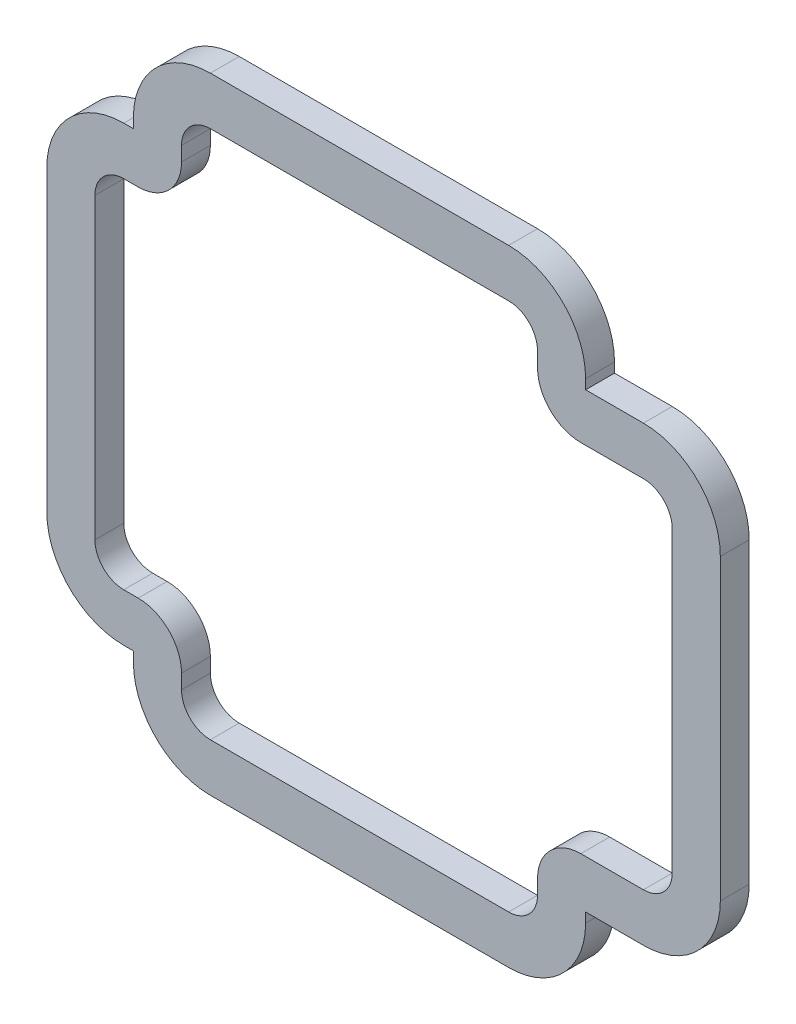
SolidWorks part; units mm, degrees
ref_plane "Plano frontal" through (0, 0, 0) normal (0, 0, 1) x (1, 0, 0)
ref_plane "Plano superior" through (0, 0, 0) normal (0, 1, 0) x (1, 0, 0)
ref_plane "Plano direito" through (0, 0, 0) normal (1, 0, 0) x (0, 0, -1)
sketch "Esboço1" plane through (0, 0, 0) normal (0, 0, 1) x (1, 0, 0)
  line L0 (46.5, -1.5) -> (46.5, -0.5)
  line L1 (46.5, -0.5) -> (52.5, -0.5)
  line L2 (60.5, 7.5) -> (60.5, 38.5)
  line L3 (52.5, 46.5) -> (46.5, 46.5)
  line L4 (46.5, 46.5) -> (46.5, 47.5)
  line L5 (38.5, 55.5) -> (7.5, 55.5)
  line L6 (-0.5, 47.5) -> (-0.5, 46.5)
  line L7 (-0.5, 46.5) -> (-1.5, 46.5)
  line L8 (-9.5, 38.5) -> (-9.5, 7.5)
  line L9 (-1.5, -0.5) -> (-0.5, -0.5)
  line L10 (-0.5, -0.5) -> (-0.5, -1.5)
  line L11 (7.5, -9.5) -> (38.5, -9.5)
  line L24 (41.5, -1.5) -> (41.5, 0)
  line L25 (46, 4.5) -> (52.5, 4.5)
  line L26 (55.5, 7.5) -> (55.5, 38.5)
  line L27 (52.5, 41.5) -> (46, 41.5)
  line L28 (41.5, 46) -> (41.5, 47.5)
  line L29 (38.5, 50.5) -> (7.5, 50.5)
  line L30 (4.5, 47.5) -> (4.5, 46)
  line L31 (0, 41.5) -> (-1.5, 41.5)
  line L32 (-4.5, 38.5) -> (-4.5, 7.5)
  line L33 (-1.5, 4.5) -> (0, 4.5)
  line L34 (4.5, 0) -> (4.5, -1.5)
  line L35 (7.5, -4.5) -> (38.5, -4.5)
  arc A2 (38.5, -9.5) -> (46.5, -1.5) centre (38.5, -1.5) ccw
  arc A3 (46.5, -0.5) -> (46.5, -0.5) centre (46.5, -0.5) ccw
  arc A4 (52.5, -0.5) -> (60.5, 7.5) centre (52.5, 7.5) ccw
  arc A5 (60.5, 38.5) -> (52.5, 46.5) centre (52.5, 38.5) ccw
  arc A6 (46.5, 46.5) -> (46.5, 46.5) centre (46.5, 46.5) ccw
  arc A7 (46.5, 47.5) -> (38.5, 55.5) centre (38.5, 47.5) ccw
  arc A8 (7.5, 55.5) -> (-0.5, 47.5) centre (7.5, 47.5) ccw
  arc A9 (-0.5, 46.5) -> (-0.5, 46.5) centre (-0.5, 46.5) ccw
  arc A10 (-1.5, 46.5) -> (-9.5, 38.5) centre (-1.5, 38.5) ccw
  arc A11 (-9.5, 7.5) -> (-1.5, -0.5) centre (-1.5, 7.5) ccw
  arc A12 (-0.5, -0.5) -> (-0.5, -0.5) centre (-0.5, -0.5) ccw
  arc A13 (-0.5, -1.5) -> (7.5, -9.5) centre (7.5, -1.5) ccw
  arc A26 (38.5, -4.5) -> (41.5, -1.5) centre (38.5, -1.5) ccw
  arc A27 (46, 4.5) -> (41.5, 0) centre (46, 0) ccw
  arc A28 (52.5, 4.5) -> (55.5, 7.5) centre (52.5, 7.5) ccw
  arc A29 (55.5, 38.5) -> (52.5, 41.5) centre (52.5, 38.5) ccw
  arc A30 (41.5, 46) -> (46, 41.5) centre (46, 46) ccw
  arc A31 (41.5, 47.5) -> (38.5, 50.5) centre (38.5, 47.5) ccw
  arc A32 (7.5, 50.5) -> (4.5, 47.5) centre (7.5, 47.5) ccw
  arc A33 (0, 41.5) -> (4.5, 46) centre (0, 46) ccw
  arc A34 (-1.5, 41.5) -> (-4.5, 38.5) centre (-1.5, 38.5) ccw
  arc A35 (-4.5, 7.5) -> (-1.5, 4.5) centre (-1.5, 7.5) ccw
  arc A36 (4.5, 0) -> (0, 4.5) centre (0, 0) ccw
  arc A37 (4.5, -1.5) -> (7.5, -4.5) centre (7.5, -1.5) ccw
  dimension "D2" = 5
extrude "Ressalto-extrusão1" add sketch "Esboço1" along normal blind 3
